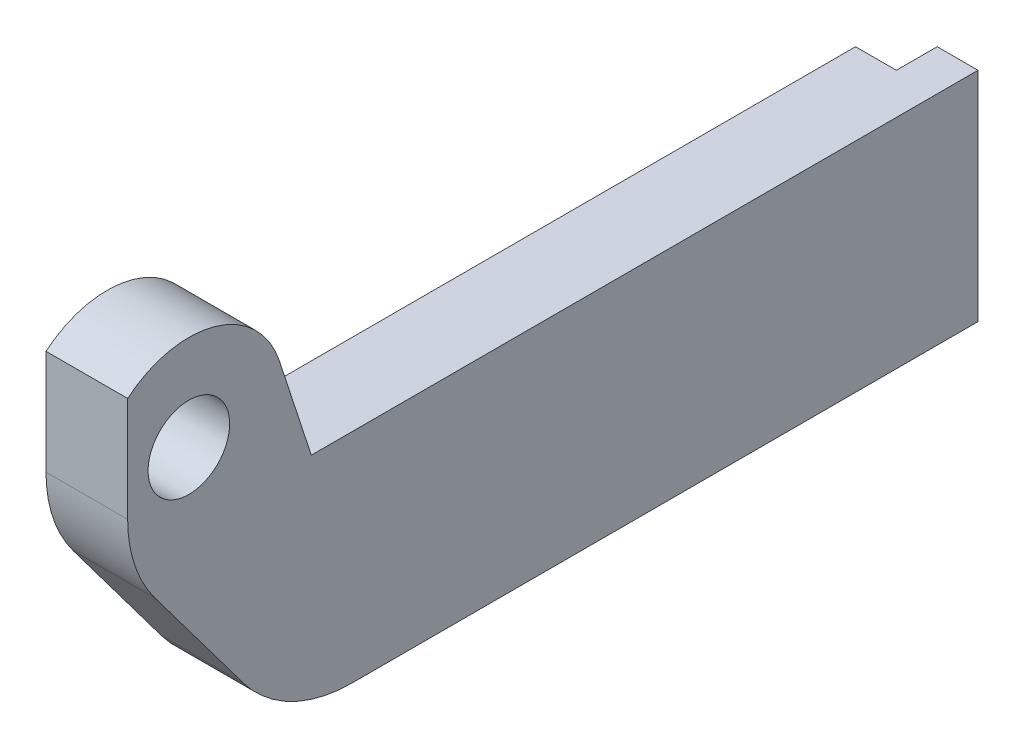
SolidWorks part; units mm, degrees
ref_plane "Front Plane" through (0, 0, 0) normal (0, 0, 1) x (1, 0, 0)
ref_plane "Top Plane" through (0, 0, 0) normal (0, 1, 0) x (1, 0, 0)
ref_plane "Right Plane" through (0, 0, 0) normal (1, 0, 0) x (0, 0, -1)
sketch "Sketch1" plane through (0, 69.5, 0) normal (0, -1, 0) x (1, 0, 0)
  line L4 (-1, 0.185) -> (-1, -25.315)
  line L5 (-1, -25.315) -> (-2.5, -25.315)
  line L6 (-2.5, -25.315) -> (-2.5, -23.815)
  line L7 (-2.5, -23.815) -> (-4, -23.815)
  line L8 (-4, -23.815) -> (-4, 0.185)
  line L9 (-4, 0.185) -> (-1, 0.185)
  line L10 (-2.5, -23.815) -> (-4, -23.815) construction
  line L11 (-1, -25.315) -> (-2.5, -25.315) construction
  line L12 (-2.5, -25.315) -> (-2.5, -23.815) construction
  line L13 (-1, 2.558) -> (-1, -25.315) construction
  line L14 (-1, 0.185) -> (0.25, 0.185) construction
  point P15 (0, 0)
  point P17 (0, 0)
  point P20 (0, 0)
  point P21 (0, 0)
  point P22 (0, 0)
  point P23 (0, 0)
  point P24 (0, 0)
  point P25 (0, 0)
extrude "Tab extrude" add sketch "Sketch1" against normal blind 8
sketch "Sketch3" plane through (-1, 0, 0) normal (-1, 0, 0) x (0, 0, 1)
  line L0 (0.185, 71.5) -> (0.185, 114.5) construction
  line L2 (0.185, 77.5) -> (0.185, 69.5) construction
  line L3 (0.185, 69.5) -> (5.935, 77.1667)
  line L6 (5.935, 82.681) -> (5.935, 77.1667)
  line L8 (0.185, 77.5) -> (0.185, 69.5)
  line L9 (6.185, 82.2361) -> (6.185, 77.7639) construction
  line L14 (-0.815, 77.5) -> (0.3584, 81.0879)
  line L15 (0.185, 77.5) -> (-23.815, 77.5) construction
  line L16 (-0.815, 77.5) -> (-0.815, 111.5) construction
  line L17 (-0.815, 77.5) -> (0.185, 77.5)
  circle A0 centre (3.685, 80) radius 1.5 construction
  circle A1 centre (3.685, 80) radius 1.5
  arc A2 (5.935, 82.681) -> (0.3584, 81.0879) centre (3.685, 80) ccw
  dimension "D1" = 0.25
extrude "Screwhole extrude" add sketch "Sketch3" along normal up to surface (3 mm away) up to face at (-4, 73.5, -11.815)
fillet "Structural rounding" radius 5 2 edges at (-2.5, 69.5, 0.185) (-2.5, 77.1667, 5.935)
